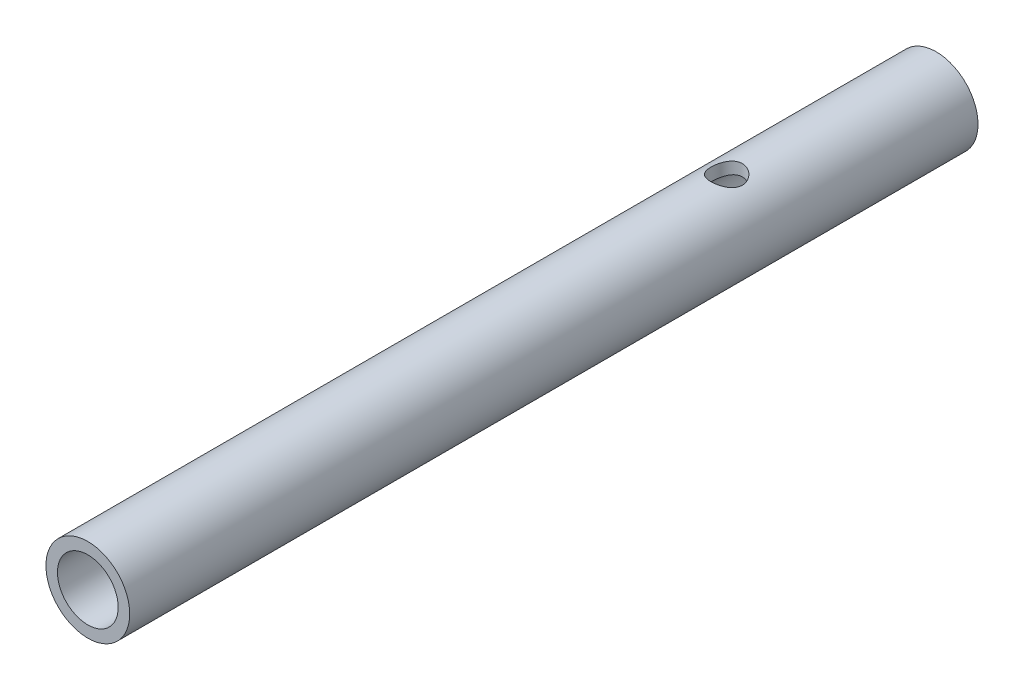
SolidWorks part; units mm, degrees
material "1060 Alloy"
ref_plane "Front Plane" through (0, 0, 0) normal (0, 0, 1) x (1, 0, 0)
ref_plane "Top Plane" through (0, 0, 0) normal (0, 1, 0) x (1, 0, 0)
ref_plane "Right Plane" through (0, 0, 0) normal (1, 0, 0) x (0, 0, -1)
sketch "Sketch1" plane through (0, 0, 0) normal (0, 0, 1) x (1, 0, 0)
  circle A0 centre (0, 0) radius 2.9
  circle A1 centre (0, 0) radius 4
  dimension "D1" = 5.8
  dimension "D2" = 8
extrude "Shaft Boss-Extrude1" add sketch "Sketch1" along normal blind 81
sketch "Sketch2" plane through (0, 0, 0) normal (0, 1, 0) x (1, 0, 0)
  line L0 (0, 10.887) -> (0, -108.8805) construction
  circle A0 centre (0, -20) radius 1.5
  dimension "D1" = 3
  dimension "D2" = 20
extrude "Cut-Extrude1" cut sketch "Sketch2" against normal up to surface and the other way up to surface up to face at (4, 0, 81) other way up to face at (4, 0, 81)
